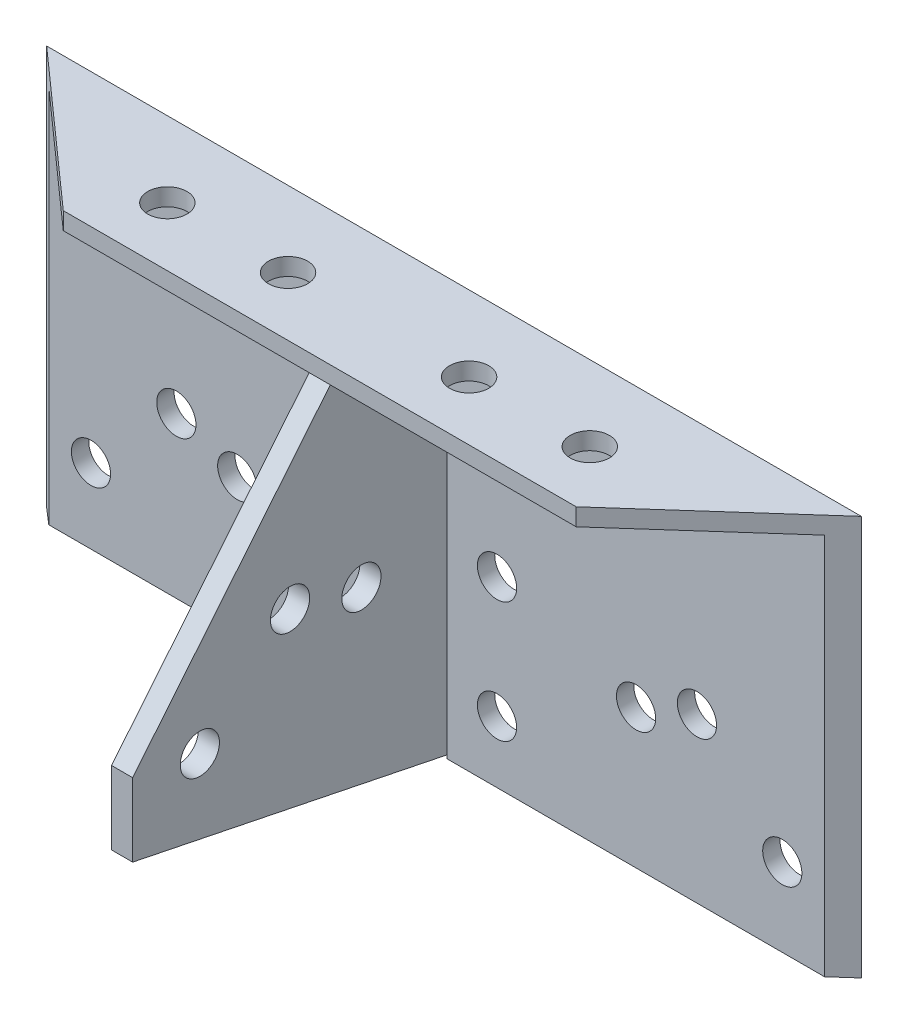
SolidWorks part; units mm, degrees
ref_plane "前视" through (0, 0, 0) normal (0, 0, 1) x (1, 0, 0)
ref_plane "上视" through (0, 0, 0) normal (0, 1, 0) x (1, 0, 0)
ref_plane "右视" through (0, 0, 0) normal (1, 0, 0) x (0, 0, -1)
sketch "草图1" plane through (0, 0, 0) normal (0, 0, 1) x (1, 0, 0)
  line L0 (270, 425.0457) -> (270, -284.5347) construction
  line L1 (0, 0) -> (540, 0)
  line L2 (0, 0) -> (0, 265)
  line L3 (0, 265) -> (540, 265)
  line L4 (540, 0) -> (540, 265)
  line L5 (270, 281) -> (-106.4291, -95.4291) construction
  line L6 (230, 208.0498) -> (230, 33.9502) construction
  line L7 (270, 147.3) -> (40.8974, 51.8974) construction
  circle A0 centre (97.4659, 108.4659) radius 13
  circle A1 centre (40.8974, 51.8974) radius 13
  circle A2 centre (499.1026, 51.8974) radius 13
  circle A3 centre (402.171, 92.2615) radius 13
  circle A4 centre (230, 121) radius 13
  circle A5 centre (230, 41) radius 13
  circle A6 centre (310, 41) radius 13
  circle A7 centre (310, 121) radius 13
  circle A8 centre (137.829, 92.2615) radius 13
  circle A9 centre (442.5341, 108.4659) radius 13
  point P7 (270, 281)
  point P28 (270, 147.3)
  dimension "D5" = 26
  dimension "D1" = 265
  dimension "D2" = 540
  dimension "D3" = 16
  dimension "D4" = 45
  dimension "D6" = 244
  dimension "D7" = 80
  dimension "D8" = 40
  dimension "D9" = 41
  dimension "D10" = 80
  dimension "D11" = 133.7
  dimension "D12" = 105
extrude "基体-拉伸" add sketch "草图1" along normal blind 11.5
sketch "草图2" plane through (0, 0, 11.5) normal (0, 0, 1) x (1, 0, 0)
  line L1 (540, 0) -> (540, 265) construction
  line L2 (0, 265) -> (540, 265)
  line L3 (0, 265) -> (0, 253.5)
  line L4 (0, 253.5) -> (540, 253.5)
  line L5 (540, 265) -> (540, 253.5)
  dimension "D1" = 11.5
extrude "凸台-拉伸1" add sketch "草图2" along normal blind 77.5
sketch "草图3" plane through (0, 265, 0) normal (0, 1, 0) x (-1, 0, 0)
  line L0 (-540, 89) -> (0, 89) construction
  line L1 (0, 89) -> (0, 0) construction
  line L2 (-270, -68.7135) -> (-270, 185.0878) construction
  line L3 (-540, 89) -> (-540, 0) construction
  line L4 (0, 0) -> (-100, 89)
  line L5 (-540, 0) -> (-440, 89)
  line L6 (0, 0) -> (0, 89)
  line L7 (0, 89) -> (-100, 89)
  line L8 (-540, 89) -> (-440, 89)
  line L9 (-540, 0) -> (-540, 89)
  point P0 (-100, 89)
  dimension "D1" = 100
extrude "切除-拉伸1" cut sketch "草图3" against normal through all
sketch "草图4" plane through (0, 265, 0) normal (0, 1, 0) x (-1, 0, 0)
  line L0 (-270, -67.5439) -> (-270, 192.1053) construction
  line L1 (-540, 0) -> (-440, 89) construction
  line L2 (-100, 89) -> (0, 0) construction
  line L3 (0, 50) -> (-540, 50) construction
  line L4 (-540, 0) -> (0, 0) construction
  circle A0 centre (-210, 50) radius 13
  circle A1 centre (-130, 50) radius 13
  circle A2 centre (-410, 50) radius 13
  circle A3 centre (-330, 50) radius 13
  dimension "D2" = 26
  dimension "D1" = 50
  dimension "D3" = 60
  dimension "D4" = 80
extrude "切除-拉伸2" cut sketch "草图4" against normal through all
sketch "草图5" plane through (0, 0, 11.5) normal (0, 0, 1) x (1, 0, 0)
  line L0 (270, 315.5409) -> (270, -66.9152) construction
  line L1 (527.0787, 0) -> (527.0787, 253.5) construction
  line L2 (12.9213, 253.5) -> (12.9213, 0) construction
  line L3 (100, 253.5) -> (440, 253.5) construction
  line L4 (263, 253.5) -> (277, 253.5)
  line L5 (263, 253.5) -> (263, 0)
  line L6 (263, 0) -> (277, 0)
  line L7 (277, 253.5) -> (277, 0)
  line L8 (12.9213, 0) -> (527.0787, 0) construction
  dimension "D1" = 14
extrude "凸台-拉伸2" add sketch "草图5" along normal blind 208.5
sketch "草图6" plane through (277, 0, 0) normal (1, 0, 0) x (0, 0, -1)
  line L0 (45, 304.1711) -> (45, -8.2567) construction
  line L1 (0, 0) -> (0, 265) construction
  line L2 (0, 265) -> (-89, 265) construction
  line L3 (45, 281) -> (-305.6244, -30.7402) construction
  line L4 (-220, 0) -> (-220, 253.5) construction
  line L5 (-89, 253.5) -> (-220, 93.5)
  line L6 (-220, 93.5) -> (-220, 253.5)
  line L7 (-220, 253.5) -> (-89, 253.5)
  line L8 (-175.4626, 84.9867) -> (115.4015, 198.8638) construction
  line L13 (-220, 0) -> (-11.5, 0) construction
  line L14 (-220, 45) -> (0, 0)
  line L15 (0, 0) -> (-220, 0)
  line L16 (-220, 0) -> (-220, 45)
  circle A0 centre (-115.6761, 138.1428) radius 13
  circle A1 centre (-175.4626, 84.9867) radius 13
  circle A2 centre (-68.3773, 126.912) radius 13
  point P4 (45, 281)
  point P13 (-220, 93.5)
  point P21 (-220, 45)
  dimension "D4" = 26
  dimension "D1" = 45
  dimension "D2" = 16
  dimension "D3" = 48.36
  dimension "D5" = 215
  dimension "D6" = 80
  dimension "D7" = 160
  dimension "D8" = 45
  dimension "D9" = 21.381
  dimension "D10" = 115
extrude "切除-拉伸3" cut sketch "草图6" against normal through all
